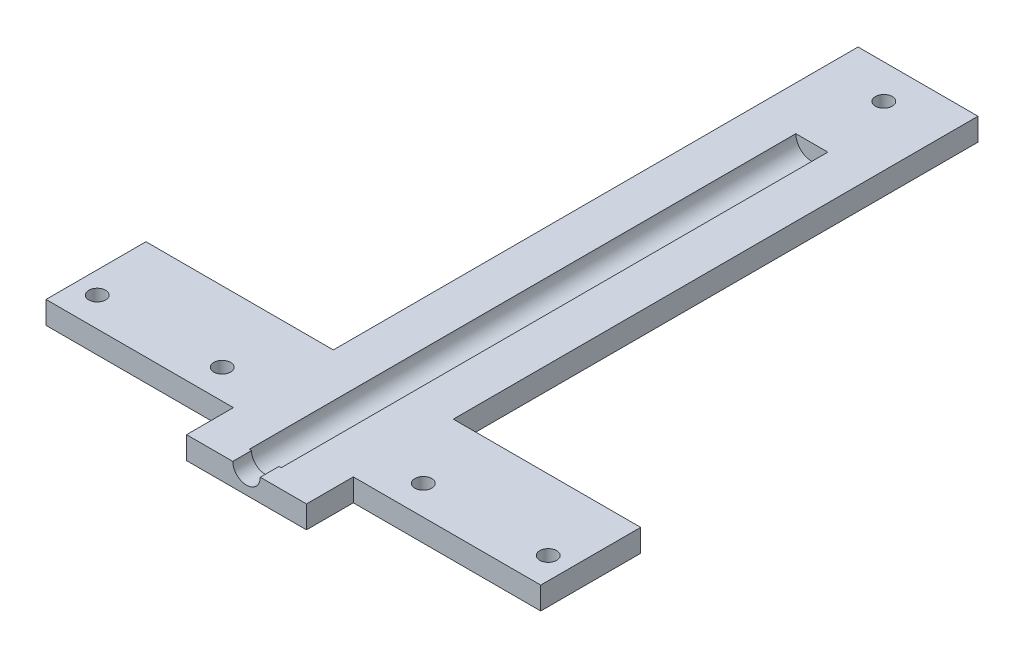
SolidWorks part; units mm, degrees
ref_plane "Front Plane" through (0, 0, 0) normal (0, 0, 1) x (1, 0, 0)
ref_plane "Top Plane" through (0, 0, 0) normal (0, 1, 0) x (1, 0, 0)
ref_plane "Right Plane" through (0, 0, 0) normal (1, 0, 0) x (0, 0, -1)
sketch "Sketch1" plane through (0, 0, 0) normal (0, 1, 0) x (1, 0, 0)
  line L4 (-100.584, 0) -> (-96.139, 0) construction
  line L9 (0, 0) -> (-100.584, 0) construction
  line L10 (0, 0) -> (0, 127)
  line L11 (0, 127) -> (-100.584, 127)
  line L12 (-100.584, 0) -> (-100.584, 127)
  line L13 (-96.139, 0) -> (-96.139, 5.969) construction
  line L14 (-96.139, 5.969) -> (-70.739, 5.969) construction
  line L15 (0, 0) -> (-4.445, 0)
  line L16 (-4.445, 0) -> (-4.445, 5.969) construction
  line L17 (-4.445, 5.969) -> (-29.845, 5.969) construction
  line L18 (-50.292, 0) -> (-50.292, 120.0404) construction
  line L19 (-100.584, 127) -> (-62.484, 127)
  line L20 (-100.584, 127) -> (-100.584, 20.32)
  line L21 (-100.584, 20.32) -> (-62.484, 20.32)
  line L22 (-62.484, 127) -> (-62.484, 20.32)
  line L23 (0, 127) -> (-38.1, 127)
  line L24 (0, 127) -> (0, 20.32)
  line L25 (0, 20.32) -> (-38.1, 20.32)
  line L26 (-38.1, 127) -> (-38.1, 20.32)
  line L27 (-53.34, 0) -> (-47.244, 0) construction
  line L28 (-50.292, 0) -> (-38.1, 0) construction
  line L33 (-100.584, 0) -> (-62.484, 0)
  line L34 (-38.1, 0) -> (-62.484, 0) construction
  line L35 (-38.1, 0) -> (-38.1, -9.525)
  line L36 (-38.1, -9.525) -> (-62.484, -9.525)
  line L37 (-62.484, 0) -> (-62.484, -9.525)
  line L38 (-38.1, 0) -> (0, 0)
  circle A0 centre (-96.139, 5.969) radius 1.7145
  circle A1 centre (-29.845, 5.969) radius 1.7145
  circle A2 centre (-4.445, 5.969) radius 1.7145
  circle A3 centre (-70.739, 5.969) radius 1.7145
  circle A4 centre (-50.292, 120.0404) radius 1.7145
  point P27 (-50.292, 0)
  dimension "D7" = 3.429
  dimension "D1" = 127
  dimension "D2" = 100.584
  dimension "D3" = 4.445
  dimension "D4" = 5.969
  dimension "D5" = 25.4
  dimension "D6" = 4.445
  dimension "D8" = 38.1
  dimension "D9" = 106.68
  dimension "D10" = 120.0404
  dimension "D11" = 12.192
  dimension "D12" = 9.525
  dimension "D13" = 24.384
extrude "Boss-Extrude1" add sketch "Sketch1" along normal blind 4.572 contours L35 L38 L15 L10 L25 L26 L11 L22 L21 L12 L33 L37 L36 A4 A3 A2 A1 A0
sketch "Sketch2" plane through (0, 0, 9.525) normal (0, 0, 1) x (1, 0, 0)
  line L0 (-38.1, 4.572) -> (-62.484, 4.572) construction
  line L1 (-53.086, 4.572) -> (-47.498, 4.572)
  arc A0 (-47.498, 4.572) -> (-53.086, 4.572) centre (-50.292, 4.572) cw
  dimension "D1" = 2.794
extrude "Cut-Extrude1" cut sketch "Sketch2" against normal blind 3.81
sketch "Sketch3" plane through (0, 0, 5.715) normal (0, 0, 1) x (1, 0, 0)
  line L0 (-47.498, 4.572) -> (-53.086, 4.572) construction
  line L1 (-38.1, 4.572) -> (-47.498, 4.572) construction
  line L2 (-53.086, 4.572) -> (-62.484, 4.572) construction
  line L3 (-53.5432, 4.572) -> (-47.0408, 4.572)
  arc A0 (-47.0408, 4.572) -> (-53.5432, 4.572) centre (-50.292, 4.572) cw
  dimension "D1" = 3.2512
extrude "Cut-Extrude2" cut sketch "Sketch3" against normal blind 111.125
